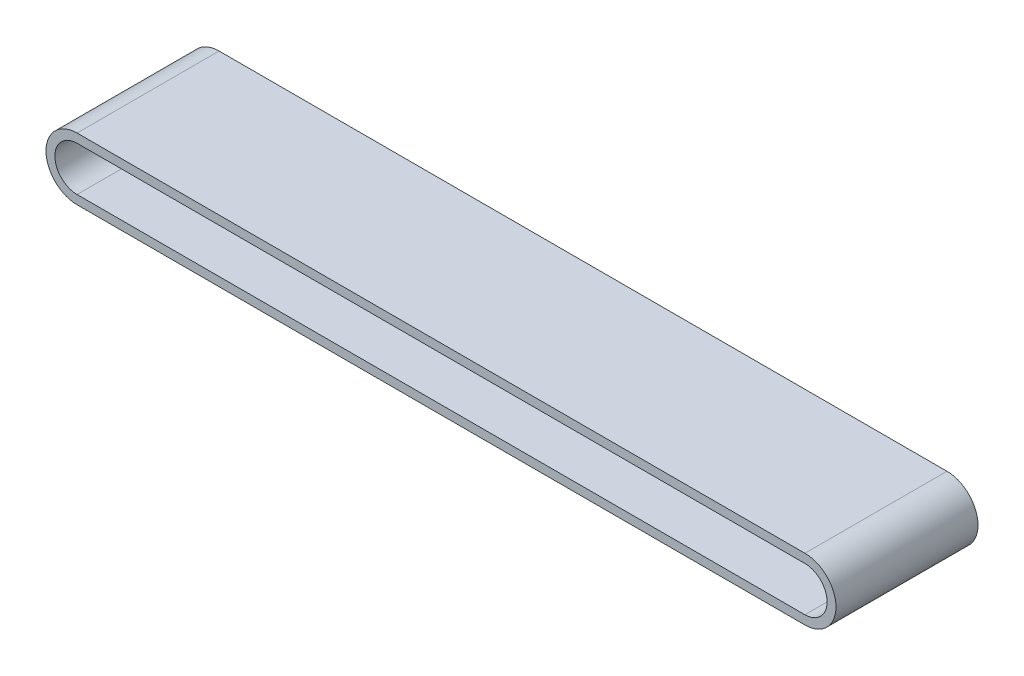
SolidWorks part; units mm, degrees
ref_plane "Front Plane" through (0, 0, 0) normal (0, 0, 1) x (1, 0, 0)
ref_plane "Top Plane" through (0, 0, 0) normal (0, 1, 0) x (1, 0, 0)
ref_plane "Right Plane" through (0, 0, 0) normal (1, 0, 0) x (0, 0, -1)
sketch "Sketch1" plane through (0, 0, 0) normal (0, 0, 1) x (1, 0, 0)
  line L0 (-244.7684, 19.2382) -> (165.2316, 19.2382)
  line L1 (-244.7684, -5.7618) -> (165.2316, -5.7618)
  line L2 (-222.2684, 6.7382) -> (-244.7684, 6.7382)
  line L3 (-244.7684, 24.2382) -> (165.2316, 24.2382)
  line L4 (-244.7684, -10.7618) -> (165.4491, -10.7604)
  arc A0 (-244.7684, 19.2382) -> (-244.7684, -5.7618) centre (-244.7684, 6.7382) ccw
  arc A1 (165.2316, -5.7618) -> (165.2316, 19.2382) centre (165.2316, 6.7382) ccw
  arc A2 (-244.7684, 24.2382) -> (-244.7684, -10.7618) centre (-244.7684, 6.7382) ccw
  arc A3 (165.4491, -10.7604) -> (165.2316, 24.2382) centre (165.2316, 6.7382) ccw
  point P2 (-14.7684, 9.3493)
  point P12 (0, 0)
  dimension "D2" = 25
  dimension "D3" = 25
  dimension "D4" = 35
  dimension "D5" = 35
  dimension "D1" = 410
extrude "Boss-Extrude1" add sketch "Sketch1" along normal blind 80 contours L4 A3 L3 A2 A1 L1 A0 L0
